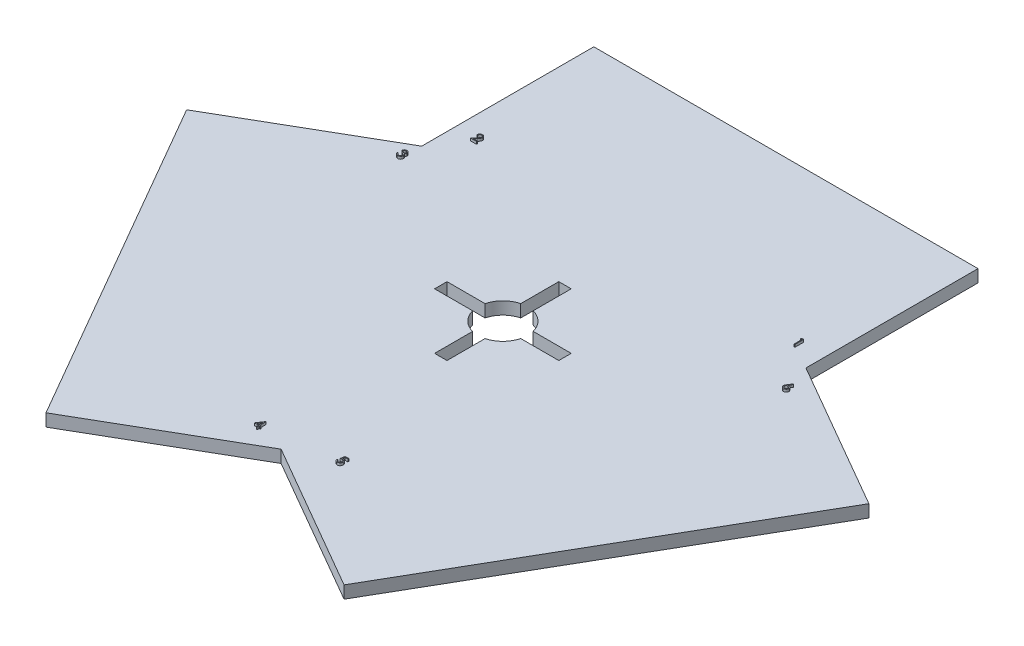
SolidWorks part; units mm, degrees
ref_plane "Front Plane" through (0, 0, 0) normal (0, 0, 1) x (1, 0, 0)
ref_plane "Top Plane" through (0, 0, 0) normal (0, 1, 0) x (1, 0, 0)
ref_plane "Right Plane" through (0, 0, 0) normal (1, 0, 0) x (0, 0, -1)
sketch "Sketch1" plane through (0, 0, 0) normal (0, 1, 0) x (1, 0, 0)
  line L0 (125, 0) -> (0, 0) construction
  line L1 (0, 0) -> (0, 125) construction
  line L2 (0, 0) -> (-52.8273, 113.2885) construction
  line L3 (-52.8273, 113.2885) -> (-52.8273, 103.9185) construction
  line L4 (-52.8273, 113.2885) -> (-7.8273, 113.2885) construction
  line L5 (-38.3273, 103.9185) -> (-67.3273, 103.9185) construction
  line L6 (-67.3273, 103.9185) -> (-67.3273, 57.9185) construction
  line L7 (-67.3273, 57.9185) -> (-38.3273, 57.9185) construction
  line L8 (-38.3273, 57.9185) -> (-38.3273, 103.9185) construction
  line L9 (67.3273, 57.9185) -> (38.3273, 57.9185) construction
  line L10 (67.3273, 103.9185) -> (67.3273, 57.9185) construction
  line L11 (38.3273, 103.9185) -> (67.3273, 103.9185) construction
  line L12 (38.3273, 57.9185) -> (38.3273, 103.9185) construction
  line L13 (0, 0) -> (52.8273, 113.2885) construction
  line L14 (52.8273, 113.2885) -> (52.8273, 103.9185) construction
  line L15 (52.8273, 113.2885) -> (7.8273, 113.2885) construction
  line L16 (124.5243, -10.8945) -> (116.4097, -6.2095) construction
  line L17 (124.5243, -10.8945) -> (102.0243, -49.8656) construction
  line L18 (109.1597, -18.7668) -> (123.6597, 6.3479) construction
  line L20 (123.6597, 6.3479) -> (83.8225, 29.3479) construction
  line L21 (83.8225, 29.3479) -> (69.3225, 4.2332) construction
  line L22 (69.3225, 4.2332) -> (109.1597, -18.7668) construction
  line L23 (16.4952, -87.2664) -> (30.9952, -62.1516) construction
  line L24 (56.3324, -110.2664) -> (16.4952, -87.2664) construction
  line L25 (70.8324, -85.1516) -> (56.3324, -110.2664) construction
  line L26 (30.9952, -62.1516) -> (70.8324, -85.1516) construction
  line L27 (71.6971, -102.394) -> (63.5824, -97.709) construction
  line L28 (71.6971, -102.394) -> (94.1971, -63.4229) construction
  line L29 (0, 0) -> (71.6971, -102.394) construction
  line L30 (0, 0) -> (124.5243, -10.8945) construction
  line L31 (-71.6971, -102.394) -> (-63.5824, -97.709) construction
  line L32 (-71.6971, -102.394) -> (-94.1971, -63.4229) construction
  line L33 (-70.8324, -85.1516) -> (-56.3324, -110.2664) construction
  line L34 (-56.3324, -110.2664) -> (-16.4952, -87.2664) construction
  line L35 (-16.4952, -87.2664) -> (-30.9952, -62.1516) construction
  line L37 (-30.9952, -62.1516) -> (-70.8324, -85.1516) construction
  line L38 (-83.8225, 29.3479) -> (-69.3225, 4.2332) construction
  line L39 (-123.6597, 6.3479) -> (-83.8225, 29.3479) construction
  line L40 (-109.1597, -18.7668) -> (-123.6597, 6.3479) construction
  line L41 (-69.3225, 4.2332) -> (-109.1597, -18.7668) construction
  line L42 (-124.5243, -10.8945) -> (-116.4097, -6.2095) construction
  line L43 (-124.5243, -10.8945) -> (-102.0243, -49.8656) construction
  line L44 (0, 0) -> (-124.5243, -10.8945) construction
  line L45 (0, 0) -> (-71.6971, -102.394) construction
  line L46 (-77.3273, 113.9185) -> (77.3273, 113.9185)
  line L47 (77.3273, 113.9185) -> (77.3273, 44.6449)
  line L48 (77.3273, 44.6449) -> (137.3199, 10.0082)
  line L49 (137.3199, 10.0082) -> (59.9927, -123.9266)
  line L50 (59.9927, -123.9266) -> (0, -89.2899)
  line L68 (0, -89.2899) -> (-59.9927, -123.9266)
  line L69 (-59.9927, -123.9266) -> (-137.3199, 10.0082)
  line L70 (-137.3199, 10.0082) -> (-77.3273, 44.6449)
  line L71 (-77.3273, 44.6449) -> (-77.3273, 113.9185)
  line L72 (-2.5, 9.6825) -> (-2.5, 25)
  line L73 (25, -2.5) -> (9.6825, -2.5)
  line L74 (25, -2.5) -> (25, 2.5)
  line L75 (25, 2.5) -> (9.6825, 2.5)
  line L76 (-25, -2.5) -> (-25, 2.5)
  line L77 (25, -2.5) -> (-25, 2.5) construction
  line L78 (25, 2.5) -> (-25, -2.5) construction
  line L79 (-2.5, -25) -> (2.5, -25)
  line L80 (-2.5, -25) -> (-2.5, -9.6825)
  line L81 (-2.5, 25) -> (2.5, 25)
  line L82 (2.5, -25) -> (2.5, -9.6825)
  line L83 (-2.5, -25) -> (2.5, 25) construction
  line L84 (-2.5, 25) -> (2.5, -25) construction
  line L85 (-9.6825, 2.5) -> (-25, 2.5)
  line L86 (-9.6825, -2.5) -> (-25, -2.5)
  line L87 (2.5, -0.25) -> (2.5, 0.25)
  line L88 (2.5, 9.6825) -> (2.5, 25)
  circle A2 centre (0, 0) radius 125 construction
  arc A3 (-2.5, 9.6825) -> (-9.6825, 2.5) centre (0, 0) ccw
  arc A4 (2.5, -9.6825) -> (9.6825, -2.5) centre (0, 0) ccw
  arc A5 (-9.6825, -2.5) -> (-2.5, -9.6825) centre (0, 0) ccw
  arc A6 (9.6825, 2.5) -> (2.5, 9.6825) centre (0, 0) ccw
  point P6 (-7.8945, 119.3282)
  point P12 (-99.394, -66.5009)
  point P14 (-52.8273, 103.9185)
  point P31 (116.4097, -6.2095)
  point P46 (-63.5824, -97.709)
  point P55 (0, 0)
  dimension "D1" = 250
  dimension "D18" = 50
  dimension "D17" = 20
  dimension "D2" = 9.37
  dimension "D3" = 45
  dimension "D4" = 29
  dimension "D5" = 46
  dimension "D6" = 50
  dimension "D7" = 3
  dimension "D9" = 10
  dimension "D10" = 10
  dimension "D11" = 10
  dimension "D12" = 10
  dimension "D13" = 10
  dimension "D14" = 10
  dimension "D15" = 10
  dimension "D16" = 10
  dimension "D8" = 10
  dimension "D19" = 50
  dimension "D20" = 5
  dimension "D21" = 5
extrude "Boss-Extrude1" add sketch "Sketch1" along normal blind 5 contours L71 L70 L69 L68 L50 L49 L48 L47 L46 A6 L75 L74 L73 A4 L82 L79 L80 A5 L86 L76 L85 A3 L72 L81 L88
sketch "Sketch2" plane through (0, 5, 0) normal (0, 1, 0) x (1, 0, 0)
  text T0 "1"
  text T1 "2"
  text T2 "3"
  text T3 "4"
  text T4 "5"
  text T5 "6"
extrude "Boss-Extrude2" add sketch "Sketch2" along normal blind 1
